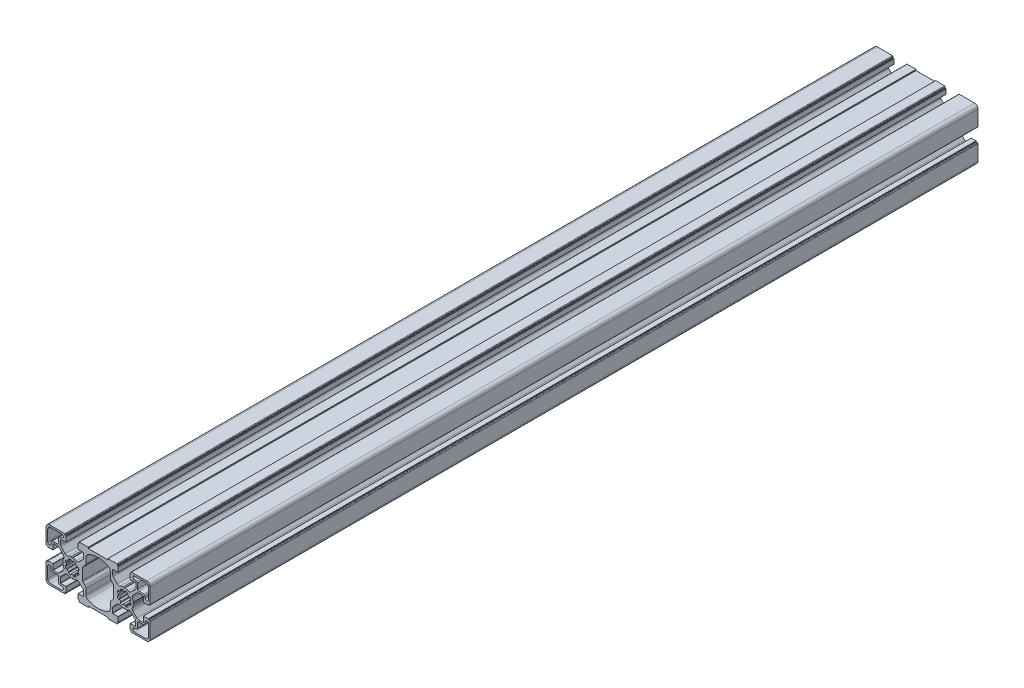
SolidWorks part; units mm, degrees
material "3.1355 (EN-AW 2024)"
ref_plane "Спереди" through (0, 0, 0) normal (0, 0, 1) x (1, 0, 0)
ref_plane "Сверху" through (0, 0, 0) normal (0, 1, 0) x (1, 0, 0)
ref_plane "Справа" through (0, 0, 0) normal (1, 0, 0) x (0, 0, -1)
sketch "Model" plane through (0, 0, 0) normal (0, 0, 1) x (1, 0, 0)
  line L1 (-43.5, 9) -> (-43.5, 18.5)
  line L2 (-41, 21) -> (-31.5002, 21)
  line L4 (-31.5002, 18) -> (-32.9945, 18)
  line L5 (-33.9945, 17) -> (-33.9945, 12.6054)
  line L6 (-34.9945, 11.6054) -> (-39.5, 11.6054)
  line L7 (-40.5, 10.6054) -> (-40.5, 9)
  line L8 (-19.3087, 4.5626) -> (-19.636, 4.0985)
  line L9 (-18.4103, 2.8765) -> (-17.9332, 3.2082)
  line L10 (-17.0103, 0.9862) -> (-17.5794, 0.8878)
  line L11 (-17.5794, -0.8878) -> (-17.0103, -0.9862)
  line L12 (-17.9332, -3.2082) -> (-18.4103, -2.8765)
  line L13 (-19.636, -4.0985) -> (-19.3087, -4.5626)
  line L14 (-21.5325, -5.4811) -> (-21.6326, -4.9242)
  line L15 (-23.3674, -4.9242) -> (-23.4675, -5.4811)
  line L16 (-25.6913, -4.5626) -> (-25.364, -4.0985)
  line L17 (-26.5897, -2.8765) -> (-27.0668, -3.2082)
  line L18 (-27.9897, -0.9862) -> (-27.4205, -0.8878)
  line L19 (-27.4205, 0.8878) -> (-27.9897, 0.9862)
  line L20 (-27.0668, 3.2082) -> (-26.5897, 2.8765)
  line L21 (-25.364, 4.0985) -> (-25.6913, 4.5626)
  line L22 (-23.4675, 5.4811) -> (-23.3674, 4.9242)
  line L23 (-21.6326, 4.9242) -> (-21.5325, 5.4811)
  line L24 (-8.5, 22.5) -> (-8.5, 21.5)
  line L25 (-8.5, 21.5) -> (8.5, 21.5)
  line L26 (8.5, 21.5) -> (8.5, 22.5)
  line L27 (-8.5, -22.5) -> (-8.5, -21.5)
  line L28 (-8.5, -21.5) -> (-5.5, -21.5)
  line L29 (-5.5, -21.5) -> (8.5, -21.5)
  line L30 (8.5, -21.5) -> (8.5, -22.5)
  line L31 (10.5, 14.21) -> (10.5, 9.4527)
  line L32 (11.3787, 7.3313) -> (13.0355, 5.6745)
  line L33 (13.3284, 4.9674) -> (13.3284, -4.9673)
  line L34 (-11.3787, 7.3313) -> (-13.0355, 5.6745)
  line L35 (10.5, -9.4526) -> (10.5, -14.21)
  line L36 (-10.5, 14.21) -> (-10.5, 9.4526)
  line L37 (-11.3787, -7.3313) -> (-13.0355, -5.6745)
  line L38 (-13.3284, -4.9674) -> (-13.3284, 4.9674)
  line L39 (30, 19.51) -> (30, 19.49)
  line L41 (-31.5, -21) -> (-41, -21)
  line L42 (-43.5, -18.5) -> (-43.5, -9.0002)
  line L44 (-40.5, -9.0002) -> (-40.5, -10.4945)
  line L45 (-39.5, -11.4945) -> (-35.1054, -11.4945)
  line L46 (-34.1054, -12.4945) -> (-34.1054, -17)
  line L47 (-33.1054, -18) -> (-31.5, -18)
  line L48 (-30.0503, -5.8456) -> (-33.6298, -9.425)
  line L49 (-35.0047, -9.9945) -> (-38.8, -9.9945)
  line L50 (-39, -9.7945) -> (-39, -5.35)
  line L51 (-39.2, -5.15) -> (-43.2, -5.15)
  line L52 (-43.5, -5.45) -> (-43.5, -5.5758)
  line L53 (-43.8, -5.8758) -> (-44.5, -5.8758)
  line L54 (-45, -6.3758) -> (-45, -19.5)
  line L55 (-42, -22.5) -> (-28.8757, -22.5)
  line L56 (-28.3757, -22) -> (-28.3757, -21.3)
  line L57 (-28.0757, -21) -> (-27.95, -21)
  line L58 (-27.65, -20.7) -> (-27.65, -16.7)
  line L59 (-27.85, -16.5) -> (-32.4054, -16.5)
  line L60 (-32.6054, -16.3) -> (-32.6054, -12.4716)
  line L61 (-32.0196, -11.0574) -> (-28.4567, -7.4945)
  line L62 (-23.2971, -7.9602) -> (-22.5, -7.5)
  line L63 (-22.5, -7.5) -> (-21.7029, -7.9602)
  line L64 (-16.6544, -7.5504) -> (-13.075, -11.1298)
  line L65 (-12.5055, -12.5048) -> (-12.5055, -16.3)
  line L66 (-12.7055, -16.5) -> (-17.15, -16.5)
  line L67 (-17.35, -16.7) -> (-17.35, -20.7)
  line L68 (-17.05, -21) -> (-16.9242, -21)
  line L69 (-16.6242, -21.3) -> (-16.6242, -22)
  line L70 (-16.1242, -22.5) -> (-8.5, -22.5)
  line L71 (-10.5, -9.4526) -> (-10.5, -14.21)
  line L76 (11.3787, -7.3313) -> (13.0355, -5.6744)
  line L77 (30.0002, -19.45) -> (30.0002, -19.55)
  line L78 (32.9945, -18) -> (31.4502, -18)
  line L79 (31.4502, -21) -> (41, -21)
  line L80 (-31.5002, 18) -> (-31.4902, 18)
  line L81 (-30.0002, 19.49) -> (-30.0002, 19.51)
  line L82 (-31.4902, 21) -> (-31.5002, 21)
  line L83 (31.5, 21) -> (31.49, 21)
  line L85 (31.49, 18) -> (31.5, 18)
  line L87 (-8.5, 22.5) -> (-16.1243, 22.5)
  line L88 (-16.6243, 22) -> (-16.6243, 21.3)
  line L89 (-16.9243, 21) -> (-17.05, 21)
  line L90 (-17.35, 20.7) -> (-17.35, 16.7)
  line L91 (-17.15, 16.5) -> (-12.5946, 16.5)
  line L92 (-12.3946, 16.3) -> (-12.3946, 12.4716)
  line L93 (-12.9804, 11.0574) -> (-16.5432, 7.4945)
  line L94 (-21.7029, 7.9602) -> (-22.5, 7.5)
  line L95 (-22.5, 7.5) -> (-23.2971, 7.9602)
  line L96 (-28.3455, 7.5503) -> (-31.925, 11.1298)
  line L97 (-32.4945, 12.5047) -> (-32.4945, 16.3)
  line L98 (-32.2945, 16.5) -> (-27.85, 16.5)
  line L99 (-27.65, 16.7) -> (-27.65, 20.7)
  line L100 (-27.95, 21) -> (-28.0757, 21)
  line L101 (-28.3757, 21.3) -> (-28.3757, 22)
  line L102 (-28.8757, 22.5) -> (-42, 22.5)
  line L103 (-45, 19.5) -> (-45, 6.3757)
  line L104 (-44.5, 5.8757) -> (-43.8, 5.8757)
  line L105 (-43.5, 5.5757) -> (-43.5, 5.45)
  line L106 (-43.2, 5.15) -> (-39.2, 5.15)
  line L107 (-39, 5.35) -> (-39, 9.9054)
  line L108 (-38.8, 10.1054) -> (-34.9716, 10.1054)
  line L109 (-33.5574, 9.5196) -> (-29.9945, 5.9567)
  line L110 (-30.4602, 0.7971) -> (-30, 0)
  line L111 (-30, 0) -> (-30.4602, -0.7971)
  line L113 (21.5325, 5.4812) -> (21.6326, 4.9242)
  line L114 (33.1054, 18) -> (31.5, 18)
  line L117 (30, 0) -> (30.4602, 0.7971)
  line L118 (32.6054, 16.3001) -> (32.6054, 12.4716)
  line L119 (27.0668, -3.2081) -> (26.5897, -2.8765)
  line L120 (33.9945, -17) -> (33.9945, -12.6054)
  line L121 (28.3456, -7.5503) -> (31.925, -11.1297)
  line L122 (45, -19.4999) -> (45, -6.3757)
  line L123 (33.5574, -9.5196) -> (29.9945, -5.9567)
  line L124 (17.35, 16.7001) -> (17.35, 20.7)
  line L126 (17.5795, 0.8879) -> (17.0103, 0.9863)
  line L127 (40.5, 9.0002) -> (40.5, 10.4945)
  line L128 (17.15, -16.5) -> (12.5946, -16.5)
  line L129 (30.0503, 5.8456) -> (33.6298, 9.425)
  line L130 (28.0757, 21.0001) -> (27.95, 21.0001)
  line L132 (26.5897, 2.8765) -> (27.0668, 3.2082)
  line L135 (39, -5.35) -> (39, -9.9053)
  line L136 (16.6544, 7.5504) -> (13.075, 11.1298)
  line L138 (19.3087, -4.5626) -> (19.636, -4.0984)
  line L139 (31.5, 21) -> (41, 21)
  line L141 (32.2945, -16.5) -> (27.85, -16.5)
  line L142 (45, 6.3758) -> (45, 19.5001)
  line L145 (23.3674, 4.9242) -> (23.4675, 5.4811)
  line L147 (12.9804, -11.0573) -> (16.5433, -7.4945)
  line L148 (39.2, 5.15) -> (43.2, 5.15)
  line L149 (32.0196, 11.0574) -> (28.4567, 7.4946)
  line L150 (25.364, -4.0984) -> (25.6913, -4.5626)
  line L151 (34.9945, -11.6054) -> (39.5, -11.6054)
  line L153 (28.8757, -22.4999) -> (42, -22.4999)
  line L154 (17.05, 21) -> (16.9243, 21)
  line L156 (17.9332, 3.2082) -> (18.4103, 2.8765)
  line L157 (39.5, 11.4945) -> (35.1054, 11.4945)
  line L159 (16.6243, -22) -> (16.6243, -21.3)
  line L160 (44.5, -5.8757) -> (43.8, -5.8757)
  line L161 (27.65, 20.7001) -> (27.65, 16.7001)
  line L163 (27.9897, 0.9863) -> (27.4205, 0.8879)
  line L165 (22.5, -7.5) -> (23.2971, -7.9601)
  line L166 (12.5055, 12.5048) -> (12.5055, 16.3001)
  line L167 (18.4103, -2.8765) -> (17.9332, -3.2081)
  line L168 (43.5, 18.5) -> (43.5, 9.0002)
  line L169 (17.35, -20.7) -> (17.35, -16.7)
  line L170 (27.65, -16.7) -> (27.65, -20.6999)
  line L171 (42, 22.5001) -> (28.8757, 22.5001)
  line L178 (16.9243, -21) -> (17.05, -21)
  line L179 (28.3757, -21.2999) -> (28.3757, -21.9999)
  line L180 (43.2, -5.15) -> (39.2, -5.15)
  line L181 (23.2971, 7.9602) -> (22.5, 7.5)
  line L182 (23.4675, -5.4811) -> (23.3674, -4.9242)
  line L183 (40.5, -10.6054) -> (40.5, -9)
  line L185 (32.4945, -12.5047) -> (32.4945, -16.3)
  line L186 (43.5, 5.45) -> (43.5, 5.5758)
  line L187 (16.6243, 21.3) -> (16.6243, 22)
  line L189 (19.636, 4.0985) -> (19.3087, 4.5626)
  line L190 (34.1054, 12.4945) -> (34.1054, 17)
  line L191 (12.3946, -16.3) -> (12.3946, -12.4715)
  line L192 (27.95, -20.9999) -> (28.0757, -20.9999)
  line L193 (35.0048, 9.9946) -> (38.8, 9.9946)
  line L194 (27.85, 16.5001) -> (32.4054, 16.5001)
  line L196 (27.4205, -0.8878) -> (27.9897, -0.9862)
  line L199 (8.5, -22.5) -> (16.1243, -22.5)
  line L200 (30.4602, -0.797) -> (30, 0)
  line L201 (12.7055, 16.5001) -> (17.15, 16.5001)
  line L205 (17.0103, -0.9862) -> (17.5795, -0.8878)
  line L208 (39, 9.7946) -> (39, 5.35)
  line L209 (28.3757, 22.0001) -> (28.3757, 21.3001)
  line L211 (25.6913, 4.5626) -> (25.364, 4.0985)
  line L212 (43.5, -9) -> (43.5, -18.5)
  line L214 (21.7029, -7.9601) -> (22.5, -7.5)
  line L215 (38.8, -10.1053) -> (34.9716, -10.1053)
  line L216 (22.5, 7.5) -> (21.7029, 7.9602)
  line L218 (21.6326, -4.9242) -> (21.5325, -5.4811)
  line L221 (43.5, -5.5757) -> (43.5, -5.45)
  line L222 (43.8, 5.8758) -> (44.5, 5.8758)
  line L223 (16.1243, 22.5) -> (8.5, 22.5)
  arc A0 (-31.5, -21) -> (-30, -19.5) centre (-31.5, -19.5) ccw
  arc A1 (-43.5, 9) -> (-42, 7.5) centre (-42, 9) ccw
  arc A2 (-41, 21) -> (-43.5, 18.5) centre (-41, 18.5) ccw
  arc A3 (-30, -19.5) -> (-31.5, -18) centre (-31.5, -19.5) ccw
  arc A4 (-31.4902, 18) -> (-30.0002, 19.49) centre (-31.4902, 19.49) ccw
  arc A5 (-32.9945, 18) -> (-33.9945, 17) centre (-32.9945, 17) ccw
  arc A6 (-34.9945, 11.6054) -> (-33.9945, 12.6054) centre (-34.9945, 12.6054) ccw
  arc A7 (-39.5, 11.6054) -> (-40.5, 10.6054) centre (-39.5, 10.6054) ccw
  arc A8 (-19.3087, 4.5626) -> (-19.4583, 5.301) centre (-19.7057, 4.8665) ccw
  arc A9 (-18.4103, 2.8765) -> (-19.636, 4.0985) centre (-22.5, 0) ccw
  arc A10 (-17.1975, 3.0565) -> (-17.9332, 3.2082) centre (-17.632, 2.8091) ccw
  arc A11 (-16.5939, 1.6142) -> (-17.1975, 3.0565) centre (-22.4765, 0) ccw
  arc A12 (-17.0103, 0.9862) -> (-16.5939, 1.6142) centre (-17.0761, 1.4818) ccw
  arc A13 (-17.5794, -0.8878) -> (-17.5794, 0.8878) centre (-22.5, 0) ccw
  arc A14 (-16.5939, -1.6142) -> (-17.0103, -0.9862) centre (-17.0761, -1.4819) ccw
  arc A15 (-17.1975, -3.0565) -> (-16.5939, -1.6142) centre (-22.4765, 0) ccw
  arc A16 (-17.9332, -3.2082) -> (-17.1975, -3.0565) centre (-17.632, -2.8091) ccw
  arc A17 (-19.636, -4.0985) -> (-18.4103, -2.8765) centre (-22.5, 0) ccw
  arc A18 (-19.4583, -5.301) -> (-19.3087, -4.5626) centre (-19.7057, -4.8665) ccw
  arc A19 (-20.9049, -5.8941) -> (-19.4583, -5.301) centre (-22.4765, 0) ccw
  arc A20 (-21.5325, -5.4811) -> (-20.9049, -5.8941) centre (-21.0373, -5.4119) ccw
  arc A21 (-23.3674, -4.9242) -> (-21.6326, -4.9242) centre (-22.5, 0) ccw
  arc A22 (-24.0951, -5.8941) -> (-23.4675, -5.4811) centre (-23.9627, -5.4119) ccw
  arc A23 (-25.5444, -5.2995) -> (-24.0951, -5.8941) centre (-22.5235, 0) ccw
  arc A24 (-25.6913, -4.5626) -> (-25.5444, -5.2995) centre (-25.2943, -4.8665) ccw
  arc A25 (-26.5897, -2.8765) -> (-25.364, -4.0985) centre (-22.5, 0) ccw
  arc A26 (-27.8025, -3.0565) -> (-27.0668, -3.2082) centre (-27.368, -2.8091) ccw
  arc A27 (-28.4068, -1.6112) -> (-27.8025, -3.0565) centre (-22.5235, 0) ccw
  arc A28 (-27.9897, -0.9862) -> (-28.4068, -1.6112) centre (-27.9239, -1.4819) ccw
  arc A29 (-27.4205, 0.8878) -> (-27.4205, -0.8878) centre (-22.5, 0) ccw
  arc A30 (-28.4068, 1.6112) -> (-27.9897, 0.9862) centre (-27.9239, 1.4818) ccw
  arc A31 (-27.8025, 3.0565) -> (-28.4068, 1.6112) centre (-22.5235, 0) ccw
  arc A32 (-27.0668, 3.2082) -> (-27.8025, 3.0565) centre (-27.368, 2.8091) ccw
  arc A33 (-25.364, 4.0985) -> (-26.5897, 2.8765) centre (-22.5, 0) ccw
  arc A34 (-25.5444, 5.2994) -> (-25.6913, 4.5626) centre (-25.2943, 4.8665) ccw
  arc A35 (-24.0951, 5.8941) -> (-25.5444, 5.2994) centre (-22.5235, 0) ccw
  arc A36 (-23.4675, 5.4811) -> (-24.0951, 5.8941) centre (-23.9627, 5.4119) ccw
  arc A37 (-21.6326, 4.9242) -> (-23.3674, 4.9242) centre (-22.5, 0) ccw
  arc A38 (-20.9049, 5.8941) -> (-21.5325, 5.4811) centre (-21.0373, 5.4119) ccw
  arc A39 (-19.4583, 5.301) -> (-20.9049, 5.8941) centre (-22.4765, 0) ccw
  arc A40 (-8.9003, -16.8631) -> (8.9003, -16.8631) centre (0, 0) ccw
  arc A41 (8.9003, 16.8631) -> (-8.9003, 16.8631) centre (0, 0) ccw
  arc A42 (-8.9003, -16.8631) -> (-10.5, -14.21) centre (-7.5, -14.21) cw
  arc A43 (8.9003, -16.8631) -> (10.5, -14.21) centre (7.5, -14.21) ccw
  arc A44 (-10.5, 14.21) -> (-8.9003, 16.8631) centre (-7.5, 14.21) cw
  arc A45 (10.5, 14.21) -> (8.9003, 16.8631) centre (7.5, 14.21) ccw
  arc A46 (13.0355, -5.6744) -> (13.3284, -4.9673) centre (12.3284, -4.9673) ccw
  arc A47 (13.0355, 5.6745) -> (13.3284, 4.9674) centre (12.3284, 4.9674) cw
  arc A48 (-13.0355, 5.6745) -> (-13.3284, 4.9674) centre (-12.3284, 4.9674) ccw
  arc A49 (-13.0355, -5.6745) -> (-13.3284, -4.9674) centre (-12.3284, -4.9674) cw
  arc A50 (10.5, 9.4527) -> (11.3787, 7.3313) centre (13.5, 9.4527) ccw
  arc A51 (11.3787, -7.3313) -> (10.5, -9.4526) centre (13.5, -9.4526) ccw
  arc A52 (-11.3787, -7.3313) -> (-10.5, -9.4526) centre (-13.5, -9.4526) cw
  arc A53 (-10.5, 9.4526) -> (-11.3787, 7.3313) centre (-13.5, 9.4526) cw
  arc A54 (-30.0002, 19.51) -> (-31.4902, 21) centre (-31.4902, 19.51) ccw
  arc A55 (-40.5, 9) -> (-42, 7.5) centre (-42, 9) cw
  arc A56 (30.0002, -19.55) -> (31.4502, -21) centre (31.4502, -19.55) ccw
  arc A57 (30.0002, -19.45) -> (31.4502, -18) centre (31.4502, -19.45) cw
  arc A58 (-43.5, -18.5) -> (-41, -21) centre (-41, -18.5) ccw
  arc A59 (-42, -7.5002) -> (-43.5, -9.0002) centre (-42, -9.0002) ccw
  arc A60 (30, 19.49) -> (31.49, 18) centre (31.49, 19.49) ccw
  arc A61 (-40.5, -10.4945) -> (-39.5, -11.4945) centre (-39.5, -10.4945) ccw
  arc A62 (-34.1054, -12.4945) -> (-35.1054, -11.4945) centre (-35.1054, -12.4945) ccw
  arc A63 (-34.1054, -17) -> (-33.1054, -18) centre (-33.1054, -17) ccw
  arc A64 (-30.0503, -5.8456) -> (-29.6716, -3.5451) centre (-31.4645, -4.4313) ccw
  arc A65 (-35.0047, -9.9945) -> (-33.6298, -9.425) centre (-35.0047, -8.05) ccw
  arc A66 (-39, -9.7945) -> (-38.8, -9.9945) centre (-38.8, -9.7945) ccw
  arc A67 (-39, -5.35) -> (-39.2, -5.15) centre (-39.2, -5.35) ccw
  arc A68 (-43.2, -5.15) -> (-43.5, -5.45) centre (-43.2, -5.45) ccw
  arc A69 (-43.8, -5.8758) -> (-43.5, -5.5758) centre (-43.8, -5.5758) ccw
  arc A70 (-44.5, -5.8758) -> (-45, -6.3758) centre (-44.5, -6.3758) ccw
  arc A71 (-45, -19.5) -> (-42, -22.5) centre (-42, -19.5) ccw
  arc A72 (-28.8757, -22.5) -> (-28.3757, -22) centre (-28.8757, -22) ccw
  arc A73 (-28.0757, -21) -> (-28.3757, -21.3) centre (-28.0757, -21.3) ccw
  arc A74 (-27.95, -21) -> (-27.65, -20.7) centre (-27.95, -20.7) ccw
  arc A75 (-27.65, -16.7) -> (-27.85, -16.5) centre (-27.85, -16.7) ccw
  arc A76 (-32.6054, -16.3) -> (-32.4054, -16.5) centre (-32.4054, -16.3) ccw
  arc A77 (-32.0196, -11.0574) -> (-32.6054, -12.4716) centre (-30.6054, -12.4716) ccw
  arc A78 (-26.134, -7.127) -> (-28.4567, -7.4945) centre (-27.0425, -8.9087) ccw
  arc A79 (-26.134, -7.127) -> (-23.2971, -7.9602) centre (-22.5, 0) ccw
  arc A80 (-21.7029, -7.9602) -> (-18.9549, -7.1717) centre (-22.5, 0) ccw
  arc A81 (-16.6544, -7.5504) -> (-18.9549, -7.1717) centre (-18.0686, -8.9646) ccw
  arc A82 (-12.5055, -12.5048) -> (-13.075, -11.1298) centre (-14.45, -12.5048) ccw
  arc A83 (-12.7055, -16.5) -> (-12.5055, -16.3) centre (-12.7055, -16.3) ccw
  arc A84 (-17.15, -16.5) -> (-17.35, -16.7) centre (-17.15, -16.7) ccw
  arc A85 (-17.35, -20.7) -> (-17.05, -21) centre (-17.05, -20.7) ccw
  arc A86 (-16.6242, -21.3) -> (-16.9242, -21) centre (-16.9242, -21.3) ccw
  arc A87 (-16.6242, -22) -> (-16.1242, -22.5) centre (-16.1242, -22) ccw
  arc A88 (31.49, 21) -> (30, 19.51) centre (31.49, 19.51) ccw
  arc A89 (-40.5, -9.0002) -> (-42, -7.5002) centre (-42, -9.0002) ccw
  arc A91 (40.5, -9) -> (42, -7.5) centre (42, -9) cw
  arc A92 (40.5, 9.0002) -> (42, 7.5002) centre (42, 9.0002) ccw
  arc A106 (-16.1243, 22.5) -> (-16.6243, 22) centre (-16.1243, 22) ccw
  arc A107 (-16.9243, 21) -> (-16.6243, 21.3) centre (-16.9243, 21.3) ccw
  arc A108 (-17.05, 21) -> (-17.35, 20.7) centre (-17.05, 20.7) ccw
  arc A109 (-17.35, 16.7) -> (-17.15, 16.5) centre (-17.15, 16.7) ccw
  arc A110 (-12.3946, 16.3) -> (-12.5946, 16.5) centre (-12.5946, 16.3) ccw
  arc A111 (-12.9804, 11.0574) -> (-12.3946, 12.4716) centre (-14.3946, 12.4716) ccw
  arc A112 (-18.866, 7.127) -> (-16.5432, 7.4945) centre (-17.9575, 8.9087) ccw
  arc A113 (-18.866, 7.127) -> (-21.7029, 7.9602) centre (-22.5, 0) ccw
  arc A114 (-23.2971, 7.9602) -> (-26.0451, 7.1716) centre (-22.5, 0) ccw
  arc A115 (-28.3455, 7.5503) -> (-26.0451, 7.1716) centre (-26.9313, 8.9645) ccw
  arc A116 (-32.4945, 12.5047) -> (-31.925, 11.1298) centre (-30.55, 12.5047) ccw
  arc A117 (-32.2945, 16.5) -> (-32.4945, 16.3) centre (-32.2945, 16.3) ccw
  arc A118 (-27.85, 16.5) -> (-27.65, 16.7) centre (-27.85, 16.7) ccw
  arc A119 (-27.65, 20.7) -> (-27.95, 21) centre (-27.95, 20.7) ccw
  arc A120 (-28.3757, 21.3) -> (-28.0757, 21) centre (-28.0757, 21.3) ccw
  arc A121 (-28.3757, 22) -> (-28.8757, 22.5) centre (-28.8757, 22) ccw
  arc A122 (-42, 22.5) -> (-45, 19.5) centre (-42, 19.5) ccw
  arc A123 (-45, 6.3757) -> (-44.5, 5.8757) centre (-44.5, 6.3757) ccw
  arc A124 (-43.5, 5.5757) -> (-43.8, 5.8757) centre (-43.8, 5.5757) ccw
  arc A125 (-43.5, 5.45) -> (-43.2, 5.15) centre (-43.2, 5.45) ccw
  arc A126 (-39.2, 5.15) -> (-39, 5.35) centre (-39.2, 5.35) ccw
  arc A127 (-38.8, 10.1054) -> (-39, 9.9054) centre (-38.8, 9.9054) ccw
  arc A128 (-33.5574, 9.5196) -> (-34.9716, 10.1054) centre (-34.9716, 8.1054) ccw
  arc A129 (-29.627, 3.634) -> (-29.9945, 5.9567) centre (-31.4087, 4.5425) ccw
  arc A130 (-29.627, 3.634) -> (-30.4602, 0.7971) centre (-22.5, 0) ccw
  arc A131 (-30.4602, -0.7971) -> (-29.6716, -3.5451) centre (-22.5, 0) ccw
  arc A132 (27.8025, 3.0565) -> (27.0668, 3.2082) centre (27.368, 2.8091) ccw
  arc A133 (17.1975, -3.0564) -> (17.9332, -3.2081) centre (17.632, -2.809) ccw
  arc A134 (43.5, -9) -> (42, -7.5) centre (42, -9) ccw
  arc A136 (16.9243, -21) -> (16.6243, -21.3) centre (16.9243, -21.3) ccw
  arc A137 (43.5, -5.5757) -> (43.8, -5.8757) centre (43.8, -5.5757) ccw
  arc A138 (26.134, 7.127) -> (23.2971, 7.9602) centre (22.5, 0) ccw
  arc A139 (20.9049, -5.894) -> (21.5325, -5.4811) centre (21.0373, -5.4119) ccw
  arc A140 (34.9945, -11.6054) -> (33.9945, -12.6054) centre (34.9945, -12.6054) ccw
  arc A142 (23.2971, -7.9601) -> (26.0451, -7.1716) centre (22.5, 0) ccw
  arc A143 (30.4602, 0.7971) -> (29.6716, 3.5451) centre (22.5, 0) ccw
  arc A144 (43.8, 5.8758) -> (43.5, 5.5758) centre (43.8, 5.5758) ccw
  arc A145 (16.6243, 21.3) -> (16.9243, 21) centre (16.9243, 21.3) ccw
  arc A146 (27.0668, -3.2081) -> (27.8025, -3.0564) centre (27.368, -2.809) ccw
  arc A147 (24.0951, -5.894) -> (25.5444, -5.2994) centre (22.5235, 0) ccw
  arc A148 (21.6326, -4.9242) -> (23.3674, -4.9242) centre (22.5, 0) ccw
  arc A149 (40.5, 10.4945) -> (39.5, 11.4945) centre (39.5, 10.4945) ccw
  arc A151 (28.3757, -21.9999) -> (28.8757, -22.4999) centre (28.8757, -21.9999) ccw
  arc A152 (32.6054, 16.3001) -> (32.4054, 16.5001) centre (32.4054, 16.3001) ccw
  arc A155 (25.6913, 4.5626) -> (25.5444, 5.2995) centre (25.2943, 4.8665) ccw
  arc A156 (25.5444, 5.2995) -> (24.0951, 5.8941) centre (22.5235, 0) ccw
  arc A159 (12.9804, -11.0573) -> (12.3946, -12.4715) centre (14.3946, -12.4715) ccw
  arc A160 (33.5574, -9.5196) -> (34.9716, -10.1053) centre (34.9716, -8.1053) ccw
  arc A161 (12.7055, 16.5001) -> (12.5055, 16.3001) centre (12.7055, 16.3001) ccw
  arc A162 (28.4069, -1.6112) -> (27.9897, -0.9862) centre (27.9239, -1.4818) ccw
  arc A163 (16.594, -1.6141) -> (17.1975, -3.0564) centre (22.4765, 0) ccw
  arc A164 (24.0951, 5.8941) -> (23.4675, 5.4811) centre (23.9627, 5.4119) ccw
  arc A165 (43.5, 18.5) -> (41, 21) centre (41, 18.5) ccw
  arc A167 (27.85, -16.5) -> (27.65, -16.7) centre (27.85, -16.7) ccw
  arc A168 (39, 5.35) -> (39.2, 5.15) centre (39.2, 5.35) ccw
  arc A169 (28.0757, 21.0001) -> (28.3757, 21.3001) centre (28.0757, 21.3001) ccw
  arc A173 (26.5897, 2.8765) -> (25.364, 4.0985) centre (22.5, 0) ccw
  arc A174 (19.636, 4.0985) -> (18.4103, 2.8765) centre (22.5, 0) ccw
  arc A175 (20.9049, 5.8941) -> (19.4584, 5.301) centre (22.4765, 0) ccw
  arc A177 (17.05, -21) -> (17.35, -20.7) centre (17.05, -20.7) ccw
  arc A178 (43.5, -5.45) -> (43.2, -5.15) centre (43.2, -5.45) ccw
  arc A179 (21.7029, 7.9602) -> (18.9549, 7.1717) centre (22.5, 0) ccw
  arc A180 (28.4069, 1.6112) -> (27.8025, 3.0565) centre (22.5235, 0) ccw
  arc A181 (19.3087, -4.5626) -> (19.4584, -5.301) centre (19.7058, -4.8665) ccw
  arc A182 (19.4584, 5.301) -> (19.3087, 4.5626) centre (19.7057, 4.8665) ccw
  arc A183 (39.5, -11.6054) -> (40.5, -10.6054) centre (39.5, -10.6054) ccw
  arc A185 (28.3456, -7.5503) -> (26.0451, -7.1716) centre (26.9313, -8.9645) ccw
  arc A186 (30.0503, 5.8456) -> (29.6716, 3.5451) centre (31.4646, 4.4314) ccw
  arc A187 (44.5, 5.8758) -> (45, 6.3758) centre (44.5, 6.3758) ccw
  arc A188 (16.6243, 22) -> (16.1243, 22.5) centre (16.1243, 22) ccw
  arc A190 (23.4675, -5.4811) -> (24.0951, -5.894) centre (23.9627, -5.4119) ccw
  arc A191 (34.1054, 12.4945) -> (35.1054, 11.4945) centre (35.1054, 12.4945) ccw
  arc A193 (42, -22.4999) -> (45, -19.4999) centre (42, -19.4999) ccw
  arc A194 (32.0196, 11.0574) -> (32.6054, 12.4716) centre (30.6054, 12.4716) ccw
  arc A197 (27.9897, 0.9863) -> (28.4069, 1.6112) centre (27.9239, 1.4819) ccw
  arc A198 (17.9332, 3.2082) -> (17.1975, 3.0565) centre (17.632, 2.8091) ccw
  arc A201 (18.866, -7.1269) -> (16.5433, -7.4945) centre (17.9575, -8.9087) ccw
  arc A202 (29.627, -3.634) -> (29.9945, -5.9567) centre (31.4087, -4.5425) ccw
  arc A203 (17.15, 16.5001) -> (17.35, 16.7001) centre (17.15, 16.7001) ccw
  arc A205 (17.0103, -0.9862) -> (16.594, -1.6141) centre (17.0762, -1.4818) ccw
  arc A207 (42, 7.5002) -> (43.5, 9.0002) centre (42, 9.0002) ccw
  arc A209 (27.65, -20.6999) -> (27.95, -20.9999) centre (27.95, -20.6999) ccw
  arc A210 (43.2, 5.15) -> (43.5, 5.45) centre (43.2, 5.45) ccw
  arc A211 (27.95, 21.0001) -> (27.65, 20.7001) centre (27.95, 20.7001) ccw
  arc A215 (17.35, -16.7) -> (17.15, -16.5) centre (17.15, -16.7) ccw
  arc A216 (39.2, -5.15) -> (39, -5.35) centre (39.2, -5.35) ccw
  arc A217 (16.6544, 7.5504) -> (18.9549, 7.1717) centre (18.0687, 8.9646) ccw
  arc A218 (25.364, -4.0984) -> (26.5897, -2.8765) centre (22.5, 0) ccw
  arc A219 (17.5795, 0.8879) -> (17.5795, -0.8878) centre (22.5, 0) ccw
  arc A220 (17.1975, 3.0565) -> (16.5932, 1.6112) centre (22.4765, 0) ccw
  arc A223 (32.4945, -12.5047) -> (31.925, -11.1297) centre (30.55, -12.5047) ccw
  arc A224 (35.0048, 9.9946) -> (33.6298, 9.425) centre (35.0048, 8.0501) ccw
  arc A225 (45, 19.5001) -> (42, 22.5001) centre (42, 19.5001) ccw
  arc A228 (18.4103, -2.8765) -> (19.636, -4.0984) centre (22.5, 0) ccw
  arc A229 (34.1054, 17) -> (33.1054, 18) centre (33.1054, 17) ccw
  arc A230 (16.1243, -22.5) -> (16.6243, -22) centre (16.1243, -22) ccw
  arc A231 (45, -6.3757) -> (44.5, -5.8757) centre (44.5, -6.3757) ccw
  arc A232 (26.134, 7.127) -> (28.4567, 7.4946) centre (27.0425, 8.9088) ccw
  arc A234 (32.9945, -18) -> (33.9945, -17) centre (32.9945, -17) ccw
  arc A236 (18.866, -7.1269) -> (21.7029, -7.9601) centre (22.5, 0) ccw
  arc A237 (29.627, -3.634) -> (30.4602, -0.797) centre (22.5, 0) ccw
  arc A238 (17.35, 20.7) -> (17.05, 21) centre (17.05, 20.7) ccw
  arc A240 (27.8025, -3.0564) -> (28.4069, -1.6112) centre (22.5235, 0) ccw
  arc A241 (19.4584, -5.301) -> (20.9049, -5.894) centre (22.4765, 0) ccw
  arc A244 (28.3757, -21.2999) -> (28.0757, -20.9999) centre (28.0757, -21.2999) ccw
  arc A245 (27.65, 16.7001) -> (27.85, 16.5001) centre (27.85, 16.7001) ccw
  arc A248 (21.5325, 5.4812) -> (20.9049, 5.8941) centre (21.0373, 5.4119) ccw
  arc A249 (23.3674, 4.9242) -> (21.6326, 4.9242) centre (22.5, 0) ccw
  arc A250 (41, -21) -> (43.5, -18.5) centre (41, -18.5) ccw
  arc A252 (12.3946, -16.3) -> (12.5946, -16.5) centre (12.5946, -16.3) ccw
  arc A253 (38.8, -10.1053) -> (39, -9.9053) centre (38.8, -9.9053) ccw
  arc A254 (12.5055, 12.5048) -> (13.075, 11.1298) centre (14.45, 12.5048) ccw
  arc A255 (27.4205, -0.8878) -> (27.4205, 0.8879) centre (22.5, 0) ccw
  arc A256 (25.5444, -5.2994) -> (25.6913, -4.5626) centre (25.2943, -4.8665) ccw
  arc A257 (16.5932, 1.6112) -> (17.0103, 0.9863) centre (17.0762, 1.4819) ccw
  arc A260 (32.2945, -16.5) -> (32.4945, -16.3) centre (32.2945, -16.3) ccw
  arc A261 (39, 9.7946) -> (38.8, 9.9946) centre (38.8, 9.7946) ccw
  arc A262 (28.8757, 22.5001) -> (28.3757, 22.0001) centre (28.8757, 22.0001) ccw
  point P118 (13.3284, -5.3816)
  point P128 (10.5, 8.21)
  point P131 (10.5, -8.21)
  point P134 (-10.5, -8.21)
  point P137 (-10.5, 8.21)
extrude "Бобышка-Вытянуть1" add sketch "Model" against normal blind 715
